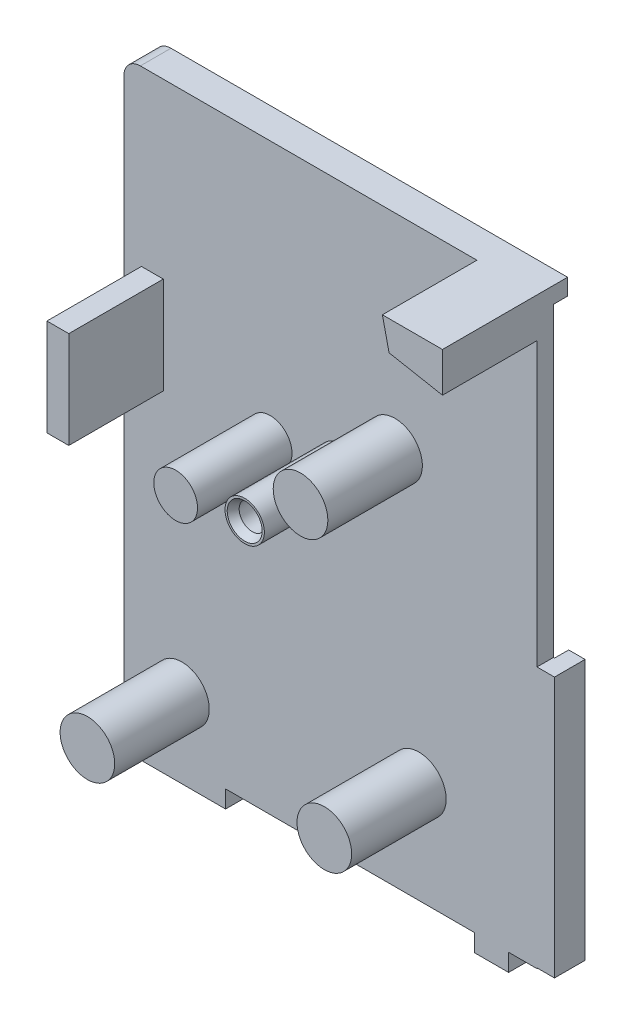
SolidWorks part; units mm, degrees
ref_plane "Front Plane" through (0, 0, 0) normal (0, 0, 1) x (1, 0, 0)
ref_plane "Top Plane" through (0, 0, 0) normal (0, 1, 0) x (1, 0, 0)
ref_plane "Right Plane" through (0, 0, 0) normal (1, 0, 0) x (0, 0, -1)
sketch "Display_support_plate_profile" plane through (0, 0, 0) normal (0, 0, 1) x (1, 0, 0)
  line L0 (-0.1, 53.4) -> (36.2, 53.4)
  line L1 (36.2, 53.4) -> (36.2, 23.9111)
  line L2 (36.2, 23.9111) -> (37.8, 23.9111)
  line L3 (37.8, 23.9111) -> (37.8, 0.06)
  line L4 (37.8, 0.06) -> (36.2, 0.06)
  line L5 (36.2, 0.06) -> (36.2, 0)
  line L6 (36.2, 0) -> (33.6, 0)
  line L7 (33.6, 0) -> (33.6, -1.6)
  line L8 (33.6, -1.6) -> (30.5, -1.6)
  line L9 (30.5, -1.6) -> (30.5, 0)
  line L10 (30.5, 0) -> (7.7, 0)
  line L11 (7.7, 0) -> (7.7, -1.6)
  line L12 (7.7, -1.6) -> (-0.1, -1.6)
  line L13 (-1.6, -0.1) -> (-1.6, 51.9)
  arc A0 (-1.6, 51.9) -> (-0.1, 53.4) centre (-0.1, 51.9) cw
  arc A1 (-0.1, -1.6) -> (-1.6, -0.1) centre (-0.1, -0.1) cw
extrude "Display_support_plate" add sketch "Display_support_plate_profile" along normal blind 1.5
sketch "Underside_locating_rim_profile" plane through (0, 0, 0) normal (0, 0, 1) x (1, 0, 0)
  line L0 (30.5, -0.1) -> (30.5, -1.6)
  line L1 (30.5, -1.6) -> (33.6, -1.6)
  line L2 (33.6, -1.6) -> (33.6, -0.1)
  line L3 (33.6, -0.1) -> (30.5, -0.1)
  line L4 (-0.1, -0.1) -> (7.7, -0.1)
  line L5 (7.7, -0.1) -> (7.7, -1.6)
  line L6 (7.7, -1.6) -> (-0.1, -1.6)
  line L7 (-1.6, -0.1) -> (-1.6, 4.496)
  line L8 (-1.6, 4.496) -> (-1.6, 51.9)
  line L9 (-0.1, 53.4) -> (36.2, 53.4)
  line L10 (36.2, 53.4) -> (36.2, 51.9)
  line L11 (36.2, 51.9) -> (-0.1, 51.9)
  line L12 (-0.1, 51.9) -> (-0.1, -0.1)
  line L13 (36.3, 23.9111) -> (37.8, 23.9111)
  line L14 (37.8, 23.9111) -> (37.8, 22.9331)
  line L15 (37.8, 22.9331) -> (37.8, 0.06)
  line L16 (37.8, 0.06) -> (36.3, 0.06)
  line L17 (36.3, 0.06) -> (36.3, 23.9111)
  arc A0 (-0.1, -1.6) -> (-1.6, -0.1) centre (-0.1, -0.1) cw
  arc A1 (-1.6, 51.9) -> (-0.1, 53.4) centre (-0.1, 51.9) cw
extrude "Underside_locating_rim" add sketch "Underside_locating_rim_profile" against normal blind 1.3
sketch "Display_relief_profile" plane through (0, 0, 0) normal (0, 0, 1) x (1, 0, 0)
  line L0 (9.55, 13.4) -> (26.55, 13.4)
  line L1 (26.55, 13.4) -> (26.55, 38.4)
  line L2 (26.55, 38.4) -> (9.55, 38.4)
  line L3 (9.55, 38.4) -> (9.55, 13.4)
extrude "Display_relief" cut sketch "Display_relief_profile" along normal blind 0.2
ref_plane "Front_1_5" through (0, 0, 1.5) normal (0, 0, 1) x (1, 0, 0)
sketch "Posts_and_retaining_stops_profile" plane through (0, 0, 1.5) normal (0, 0, 1) x (1, 0, 0)
  line L0 (0, 28.6877) -> (2, 28.6877)
  line L1 (2, 28.6877) -> (2, 37.5553)
  line L2 (2, 37.5553) -> (0, 37.5553)
  line L3 (0, 37.5553) -> (0, 28.6877)
  line L4 (21.6874, 36.6015) -> (21.6269, 36.5529)
  line L5 (21.6269, 36.5529) -> (21.6023, 36.5332)
  line L6 (17.0031, 32.1869) -> (17.0214, 32.2004)
  line L7 (17.0214, 32.2004) -> (17.0665, 32.2334)
  line L8 (9.8297, 30.0644) -> (9.8176, 30.0036)
  line L9 (9.8176, 30.0036) -> (9.8127, 29.9789)
  line L10 (36.2, 49.7742) -> (36.2, 53.4)
  line L11 (36.2, 53.4) -> (32.2901, 53.4)
  line L12 (32.2901, 53.4) -> (30.7007, 53.4)
  line L13 (30.7007, 53.4) -> (31.3132, 50.6905)
  line L14 (31.3132, 50.6905) -> (36.2, 49.7742)
  arc A0 (20.86, 33.763) -> (21.6874, 36.6015) centre (23.2093, 34.6181) ccw
  arc A1 (21.6023, 36.5332) -> (20.86, 33.763) centre (23.2093, 34.6181) ccw
  circle A2 centre (3.7063, 5.5631) radius 2.5
  arc A3 (16.3416, 30.3694) -> (17.0031, 32.1869) centre (18.099, 30.7589) cw
  arc A4 (17.0665, 32.2334) -> (16.3416, 30.3694) centre (18.099, 30.7589) cw
  circle A5 centre (25.3882, 9.2649) radius 2.5
  arc A6 (12.9998, 28.0448) -> (9.8297, 30.0644) centre (11.7823, 29.6315) ccw
  arc A7 (9.8127, 29.9789) -> (12.9998, 28.0448) centre (11.7823, 29.6315) ccw
extrude "Posts_and_retaining_stops" add sketch "Posts_and_retaining_stops_profile" along normal blind 8.65
ref_plane "Front_10_15" through (0, 0, 10.15) normal (0, 0, 1) x (1, 0, 0)
sketch "Locating_post_bore_profile" plane through (0, 0, 10.15) normal (0, 0, 1) x (1, 0, 0)
  circle A0 centre (18.0989, 30.7589) radius 1.2
extrude "Locating_post_bore" cut sketch "Locating_post_bore_profile" against normal blind 8.65
sketch "Bore_entry_chamfer_profile" plane through (0, 0, 10.15) normal (0, 0, 1) x (1, 0, 0)
  circle A0 centre (18.0989, 30.7589) radius 1.6
extrude "Bore_entry_chamfer" cut sketch "Bore_entry_chamfer_profile" against normal blind 0.6928 draft 30
